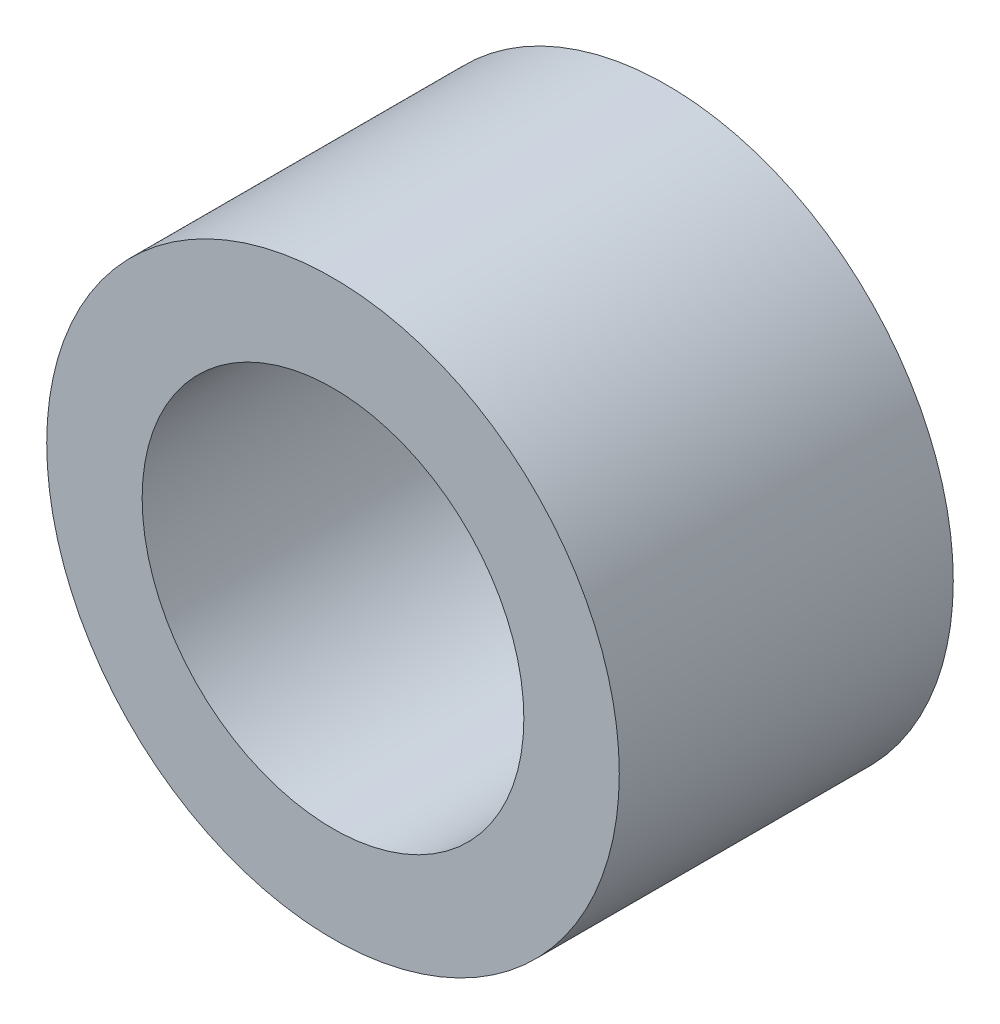
SolidWorks part; units mm, degrees
ref_plane "Front Plane" through (0, 0, 0) normal (0, 0, 1) x (1, 0, 0)
ref_plane "Top Plane" through (0, 0, 0) normal (0, 1, 0) x (1, 0, 0)
ref_plane "Right Plane" through (0, 0, 0) normal (1, 0, 0) x (0, 0, -1)
sketch "Sketch1" plane through (0, 0, 0) normal (0, 0, 1) x (1, 0, 0)
  circle A0 centre (0, 0) radius 10
  circle A1 centre (0, 0) radius 15
  dimension "D1" = 20
  dimension "D2" = 30
extrude "Boss-Extrude1" add sketch "Sketch1" against normal blind 17.5
scale "Scale1" scale about origin uniform scaling yes scale factor 0.5
